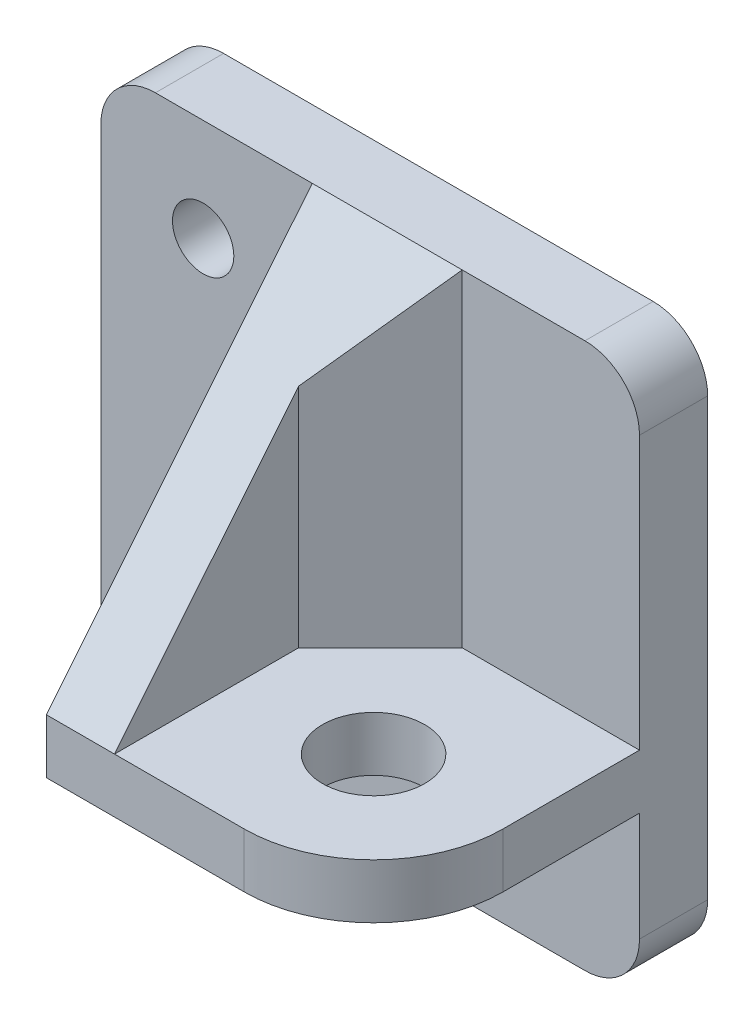
SolidWorks part; units mm, degrees
material "3D printed plastic"
ref_plane "Front Plane" through (0, 0, 0) normal (0, 0, 1) x (1, 0, 0)
ref_plane "Top Plane" through (0, 0, 0) normal (0, 1, 0) x (1, 0, 0)
ref_plane "Right Plane" through (0, 0, 0) normal (1, 0, 0) x (0, 0, -1)
sketch "Sketch1" plane through (0, 0, 0) normal (0, 0, 1) x (1, 0, 0)
  line L0 (0, -12.5) -> (0, 12.5) construction
  line L1 (-7.5, 20) -> (32, 20)
  line L2 (-7.5, 20) -> (-7.5, -20)
  line L3 (-7.5, -20) -> (32, -20)
  line L4 (32, 20) -> (32, -20)
  line L5 (0, 0) -> (-7.5, 0) construction
  circle A0 centre (0, 12.5) radius 2.25
  circle A1 centre (0, -12.5) radius 2.25
  dimension "D4" = 4.5
  dimension "D1" = 25
  dimension "D2" = 40
  dimension "D3" = 7.5
  dimension "D5" = 32
extrude "Boss-Extrude1" add sketch "Sketch1" along normal blind 5
sketch "Sketch2" plane through (0, -20, 0) normal (0, -1, 0) x (1, 0, 0)
  line L0 (32, 5) -> (13, 5)
  line L1 (-7.5, 5) -> (32, 5) construction
  line L2 (13, 5) -> (13, 24.5)
  line L3 (32, 15) -> (32, 5)
  line L4 (-7.5, 0) -> (32, 0) construction
  line L5 (22.5, 24.5) -> (13, 24.5)
  arc A0 (22.5, 24.5) -> (32, 15) centre (22.5, 15) cw
  circle A1 centre (22.5, 15) radius 3.75
  dimension "D1" = 7.5
  dimension "D2" = 15
  dimension "D3" = 22.5
extrude "Boss-Extrude2" add sketch "Sketch2" against normal blind 4 from offset 12 offset against normal yes
sketch "Sketch3" plane through (13, 0, 0) normal (-1, 0, 0) x (0, 0, 1)
  line L0 (24.5, -4) -> (5, 20)
  line L1 (5, -8) -> (24.5, -8)
  line L2 (5, -8) -> (5, -4)
  line L3 (5, -4) -> (24.5, -4) construction
  line L4 (24.5, -8) -> (24.5, -4)
  line L5 (5, 20) -> (5, -4)
  line L6 (5, 20) -> (0, 20) construction
extrude "Boss-Extrude3" add sketch "Sketch3" along normal blind 5
fillet "Fillet1" radius 4 4 edges at (32, 20, 2.5) (-7.5, -20, 2.5) (-7.5, 20, 2.5) (32, -20, 2.5)
chamfer "Chamfer2" distance 6 angle 45 1 edges at (13, 8, 5)
